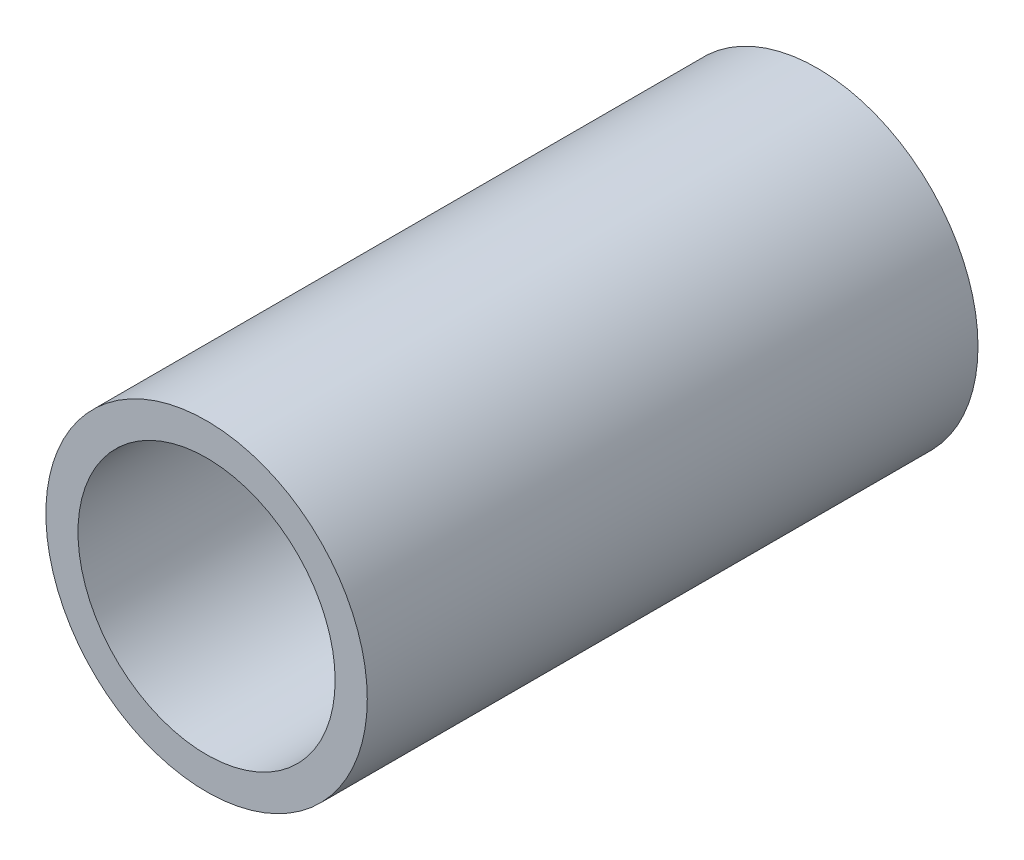
SolidWorks part; units mm, degrees
material "AISI 1045 강, 냉간압연"
ref_plane "정면" through (0, 0, 0) normal (0, 0, 1) x (1, 0, 0)
ref_plane "윗면" through (0, 0, 0) normal (0, 1, 0) x (1, 0, 0)
ref_plane "우측면" through (0, 0, 0) normal (1, 0, 0) x (0, 0, -1)
sketch "스케치1" plane through (0, 0, 0) normal (0, 0, 1) x (1, 0, 0)
  circle A0 centre (0, 0) radius 5
  circle A1 centre (0, 0) radius 4
  dimension "D1" = 10
  dimension "D2" = 8
extrude "보스-돌출1" add sketch "스케치1" along normal blind 19
